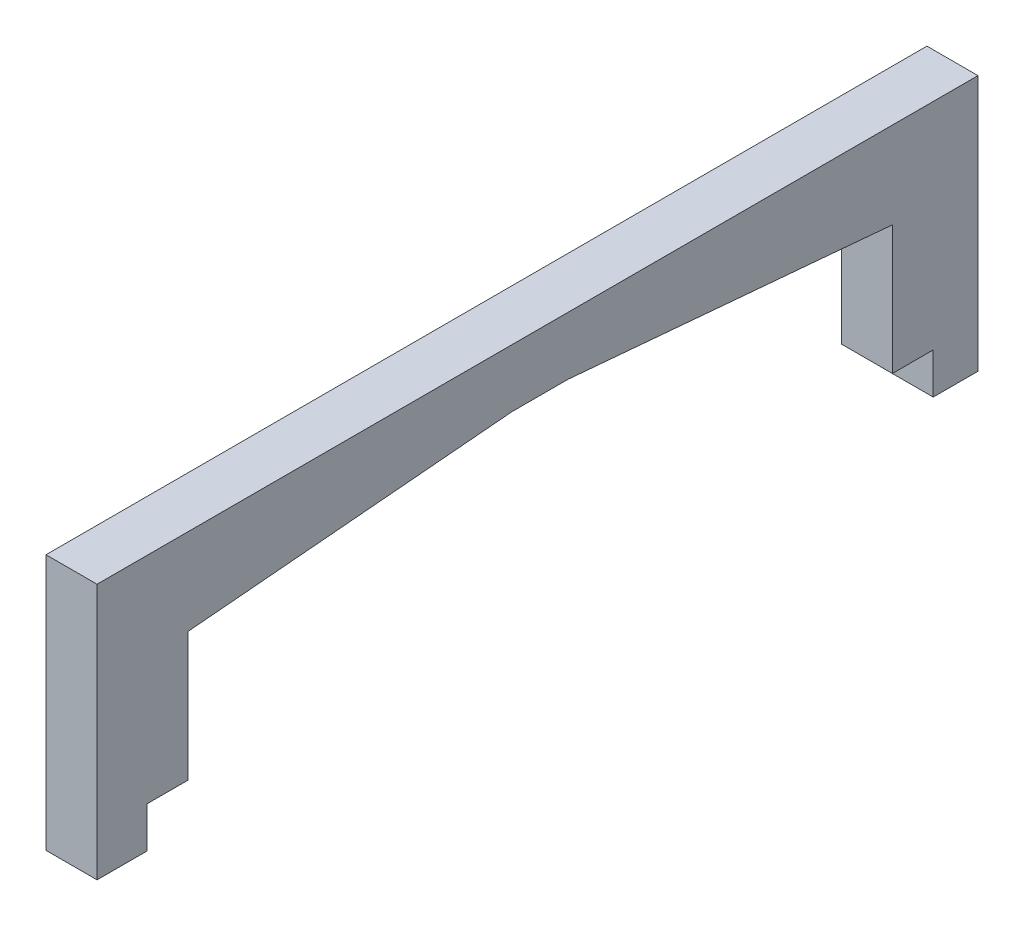
SolidWorks part; units mm, degrees
ref_plane "Plano frontal" through (0, 0, 0) normal (0, 0, 1) x (1, 0, 0)
ref_plane "Plano superior" through (0, 0, 0) normal (0, 1, 0) x (1, 0, 0)
ref_plane "Plano direito" through (0, 0, 0) normal (1, 0, 0) x (0, 0, -1)
sketch "Esboço2" plane through (0, 0, 0) normal (1, 0, 0) x (0, 0, -1)
  line L0 (-76.5, -37.173) -> (-86.2714, -37.173)
  line L1 (69.5, -29.1699) -> (77.5, -29.1699)
  line L2 (77.5, -37.173) -> (77.5, -29.1699)
  line L3 (86.2714, -37.173) -> (77.5, -37.173)
  line L7 (-76.5, -37.173) -> (-76.5, -29.1699)
  line L9 (-76.5, -29.1699) -> (-68.5, -29.1699)
  line L12 (86.2714, -37.173) -> (86.2714, 12.9759)
  line L13 (-68.5, -3.948) -> (-68.5, -29.1699)
  line L14 (-4.9782, 1.6094) -> (-68.5, -3.948)
  line L15 (-4.9782, 1.6094) -> (0, 1.6094)
  line L16 (5.9782, 1.6094) -> (0, 1.6094)
  line L17 (5.9782, 1.6094) -> (69.5, -3.948)
  line L18 (69.5, -3.948) -> (69.5, -29.1699)
  line L19 (86.2714, 12.9759) -> (-86.2714, 12.9759)
  line L20 (-86.2714, -37.173) -> (-86.2714, 12.9759)
  dimension "D1" = 8
  dimension "D2" = 8
  dimension "D3" = 138
  dimension "D5" = 8.0032
  dimension "D4" = 8.0032
extrude "Ressalto-extrusão2" add sketch "Esboço2" along normal blind 10
